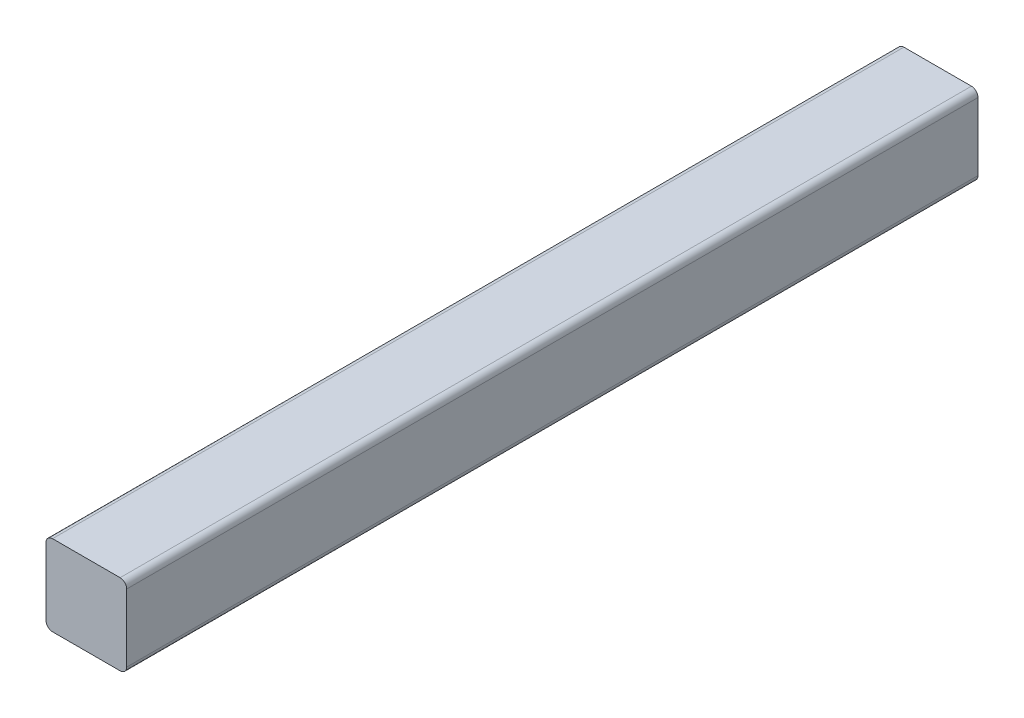
SolidWorks part; units mm, degrees
ref_plane "Front" through (0, 0, 0) normal (0, 0, 1) x (1, 0, 0)
ref_plane "Top" through (0, 0, 0) normal (0, 1, 0) x (1, 0, 0)
ref_plane "Right" through (0, 0, 0) normal (1, 0, 0) x (0, 0, -1)
sketch "Sketch2" plane through (0, 0, 0) normal (0, 0, 1) x (1, 0, 0)
  line L1 (0.25, 0) -> (2.83, 0)
  line L2 (0, 0.25) -> (0, 2.83)
  line L3 (0.25, 3.08) -> (2.83, 3.08)
  line L4 (3.08, 0.25) -> (3.08, 2.83)
  arc A0 (2.83, 0) -> (3.08, 0.25) centre (2.83, 0.25) ccw
  arc A1 (0, 0.25) -> (0.25, 0) centre (0.25, 0.25) ccw
  arc A2 (2.83, 3.08) -> (3.08, 2.83) centre (2.83, 2.83) cw
  arc A3 (0.25, 3.08) -> (0, 2.83) centre (0.25, 2.83) ccw
  point P9 (0, 0)
  dimension "D1" = 0.25
extrude "Boss-Extrude1" add sketch "Sketch2" along normal blind 32.5
sketch "Sketch4" plane through (0, 0, 0) normal (0, 0, -1) x (-1, 0, 0)
  circle A0 centre (-1.54, 1.54) radius 0.5
extrude "Boss-Extrude2" add sketch "Sketch4" along normal blind 1
